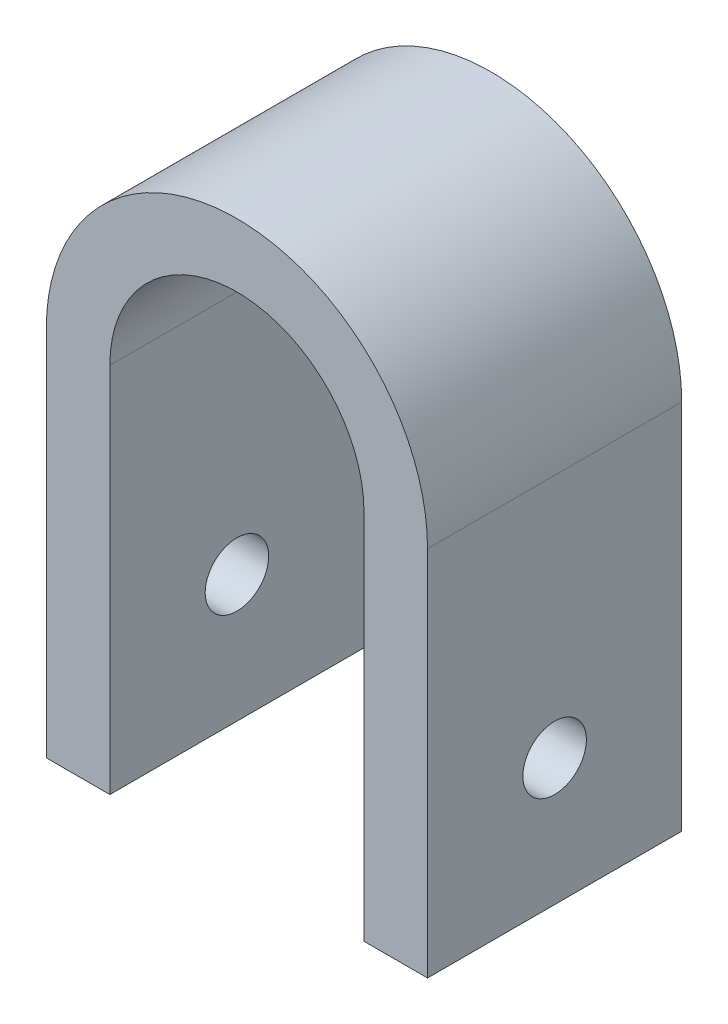
SolidWorks part; units mm, degrees
ref_plane "Front Plane" through (0, 0, 0) normal (0, 0, 1) x (1, 0, 0)
ref_plane "Top Plane" through (0, 0, 0) normal (0, 1, 0) x (1, 0, 0)
ref_plane "Right Plane" through (0, 0, 0) normal (1, 0, 0) x (0, 0, -1)
sketch "Sketch1" plane through (0, 0, 0) normal (0, 0, 1) x (1, 0, 0)
  line L0 (-4, 0) -> (-4, -11.7015)
  line L1 (-4, -5.7446) -> (-4, -25) construction
  line L3 (4, -21.6) -> (4, -5.7446) construction
  line L4 (-6, 0) -> (-6, -11.7015)
  line L5 (-6, -11.7015) -> (-4, -11.7015)
  line L6 (4, 0) -> (4, -11.7015)
  line L7 (6, 0) -> (6, -11.7015)
  line L8 (6, -11.7015) -> (4, -11.7015)
  arc A0 (4, 0) -> (-4, 0) centre (0, 0) ccw
  arc A1 (6, 0) -> (-6, 0) centre (0, 0) ccw
  dimension "D2" = 12
extrude "Boss-Extrude1" add sketch "Sketch1" along normal blind 8
sketch "Sketch2" plane through (-6, 0, 0) normal (-1, 0, 0) x (0, 0, 1)
  line L0 (0, -11.7015) -> (4, -7.7015) construction
  line L1 (4, -7.7015) -> (8, -11.7015) construction
  line L2 (8, -11.7015) -> (0, -11.7015) construction
  circle A0 centre (4, -7.7015) radius 1
  dimension "D2" = 2
  dimension "D1" = 4
extrude "Cut-Extrude1" cut sketch "Sketch2" against normal through all
